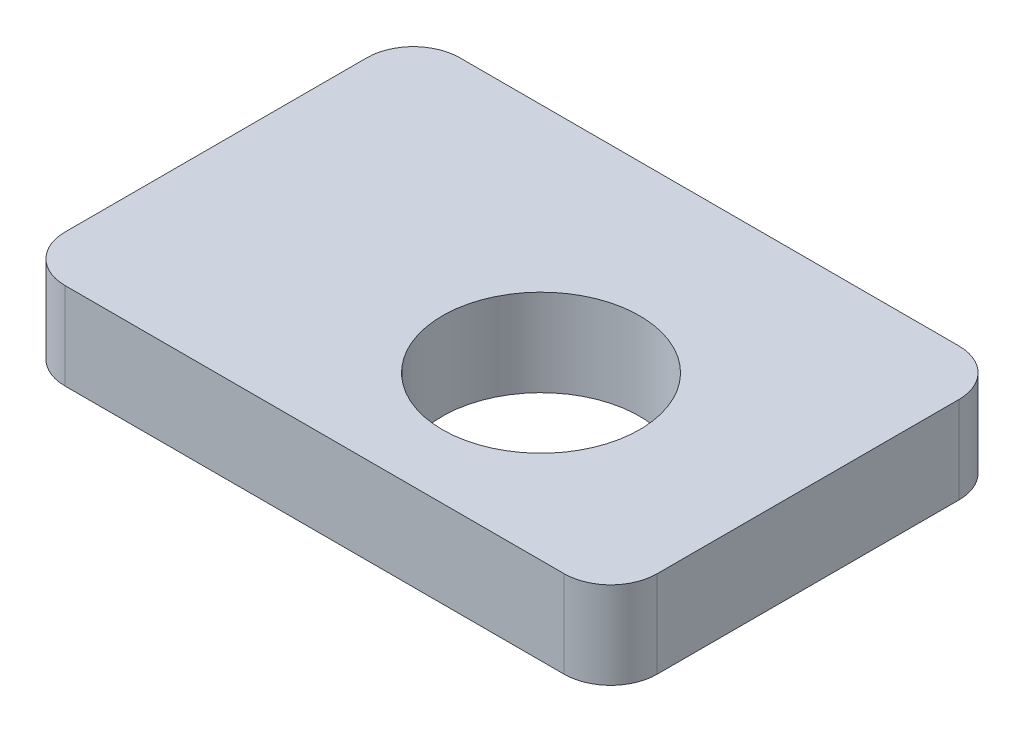
SolidWorks part; units mm, degrees
ref_plane "Front Plane" through (0, 0, 0) normal (0, 0, 1) x (1, 0, 0)
ref_plane "Top Plane" through (0, 0, 0) normal (0, 1, 0) x (1, 0, 0)
ref_plane "Right Plane" through (0, 0, 0) normal (1, 0, 0) x (0, 0, -1)
sketch "Sketch1" plane through (0, 0, 0) normal (0, 1, 0) x (1, 0, 0)
  line L0 (0, 0) -> (20, 0) construction
  line L1 (0, 0) -> (-31, 0) construction
  line L2 (-31, 0) -> (-31, 20)
  line L3 (-31, 20) -> (20, 20)
  line L4 (20, 20) -> (20, 0)
  line L5 (20, 0) -> (20, -14)
  line L6 (20, -14) -> (-31, -14)
  line L7 (-31, -14) -> (-31, 0)
  circle A0 centre (0, 0) radius 8.5
  dimension "D1" = 17
  dimension "D2" = 20
  dimension "D3" = 14
  dimension "D4" = 31
  dimension "D5" = 20
extrude "Boss-Extrude1" add sketch "Sketch1" along normal blind 7.5
fillet "Fillet1" radius 4 4 edges at (-31, 3.75, -20) (20, 3.75, -20) (20, 3.75, 14) (-31, 3.75, 14)
